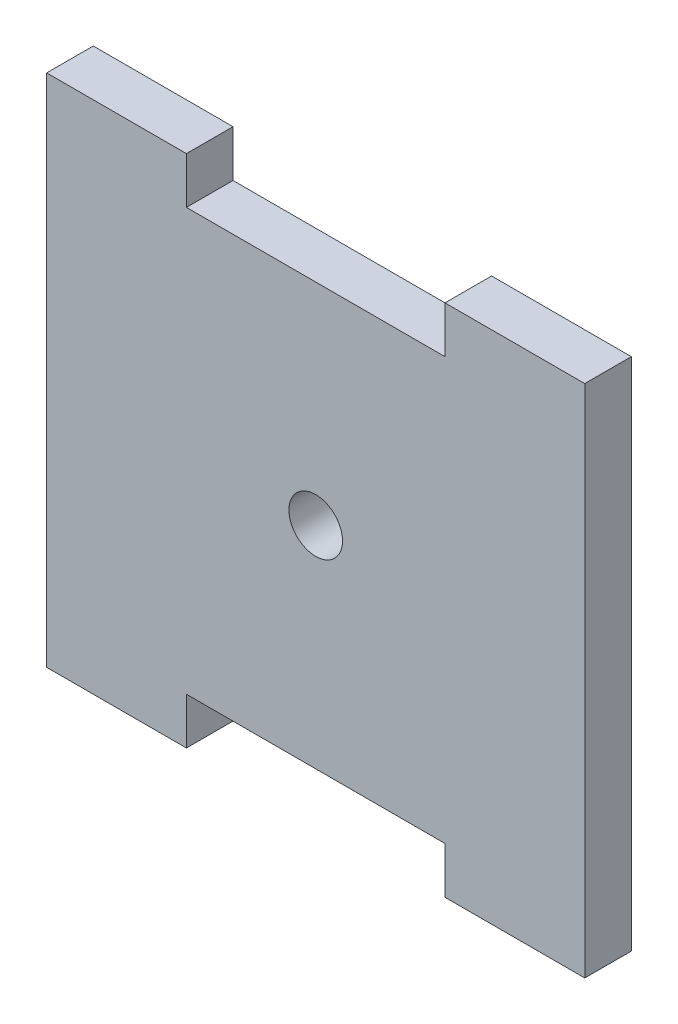
SolidWorks part; units mm, degrees
ref_plane "前视基准面" through (0, 0, 0) normal (0, 0, 1) x (1, 0, 0)
ref_plane "上视基准面" through (0, 0, 0) normal (0, 1, 0) x (1, 0, 0)
ref_plane "右视基准面" through (0, 0, 0) normal (1, 0, 0) x (0, 0, -1)
sketch "草图1" plane through (0, 0, 0) normal (0, 0, 1) x (1, 0, 0)
  line L0 (0, 0) -> (17.1, 0) construction
  line L1 (8.55, 0) -> (8.55, 1.7609) construction
  line L2 (-3, 1) -> (3, 1)
  line L3 (-3, 1) -> (-3, -1)
  line L4 (-3, -1) -> (3, -1) construction
  line L5 (3, 1) -> (3, -1)
  line L6 (-3, 1) -> (3, -1) construction
  line L7 (-3, -1) -> (3, 1) construction
  line L8 (14.1, 1) -> (14.1, -1)
  line L9 (20.1, 1) -> (20.1, -1)
  line L10 (20.1, 1) -> (14.1, 1)
  line L12 (-4.7034, -10.05) -> (23.2867, -10.05) construction
  line L13 (-3, -19.1) -> (3, -21.1) construction
  line L14 (-3, -21.1) -> (3, -19.1) construction
  line L15 (-3, -19.1) -> (3, -19.1) construction
  line L16 (8.55, -20.1) -> (8.55, -21.8609) construction
  line L17 (0, -20.1) -> (17.1, -20.1) construction
  line L19 (20.1, -21.1) -> (14.1, -21.1)
  line L20 (20.1, -21.1) -> (20.1, -19.1)
  line L21 (14.1, -21.1) -> (14.1, -19.1)
  line L22 (3, -21.1) -> (3, -19.1)
  line L23 (-3, -21.1) -> (-3, -19.1)
  line L24 (-3, -21.1) -> (3, -21.1)
  line L25 (-3, -19.1) -> (-3, -1)
  line L26 (20.1, -1) -> (20.1, -19.1)
  line L27 (8.55, -1) -> (8.55, -19.1) construction
  line L28 (6.45, -1) -> (6.45, -4.2) construction
  line L29 (6.45, -4.2) -> (5.05, -4.2) construction
  line L30 (5.05, -4.2) -> (5.05, -7.4) construction
  line L31 (5.05, -7.4) -> (12.05, -7.4) construction
  line L32 (3, -1) -> (6.45, -1) construction
  line L33 (14.1, -1) -> (10.65, -1) construction
  line L34 (10.65, -4.2) -> (12.05, -4.2) construction
  line L35 (12.05, -4.2) -> (12.05, -7.4) construction
  line L36 (10.65, -1) -> (10.65, -4.2) construction
  line L37 (3, -19.1) -> (6.45, -19.1) construction
  line L38 (14.1, -19.1) -> (10.65, -19.1) construction
  line L39 (10.65, -19.1) -> (10.65, -15.9) construction
  line L40 (6.45, -19.1) -> (6.45, -15.9) construction
  line L41 (6.45, -15.9) -> (5.05, -15.9) construction
  line L42 (10.65, -15.9) -> (12.05, -15.9)
  line L43 (12.05, -15.9) -> (12.05, -12.7) construction
  line L44 (5.05, -15.9) -> (5.05, -12.7) construction
  line L45 (5.05, -12.7) -> (12.05, -12.7) construction
  line L46 (3, -1) -> (14.1, -1)
  line L47 (3, -19.1) -> (14.1, -19.1)
  circle A0 centre (8.55, -10.05) radius 1.15
  point P40 (8.55, -7.4)
  dimension "D5" = 3.5
  dimension "D1" = 17.1
  dimension "D2" = 2
  dimension "D3" = 6
  dimension "D4" = 3.2
  dimension "D6" = 2.1
extrude "凸台-拉伸1" add sketch "草图1" along normal blind 2
